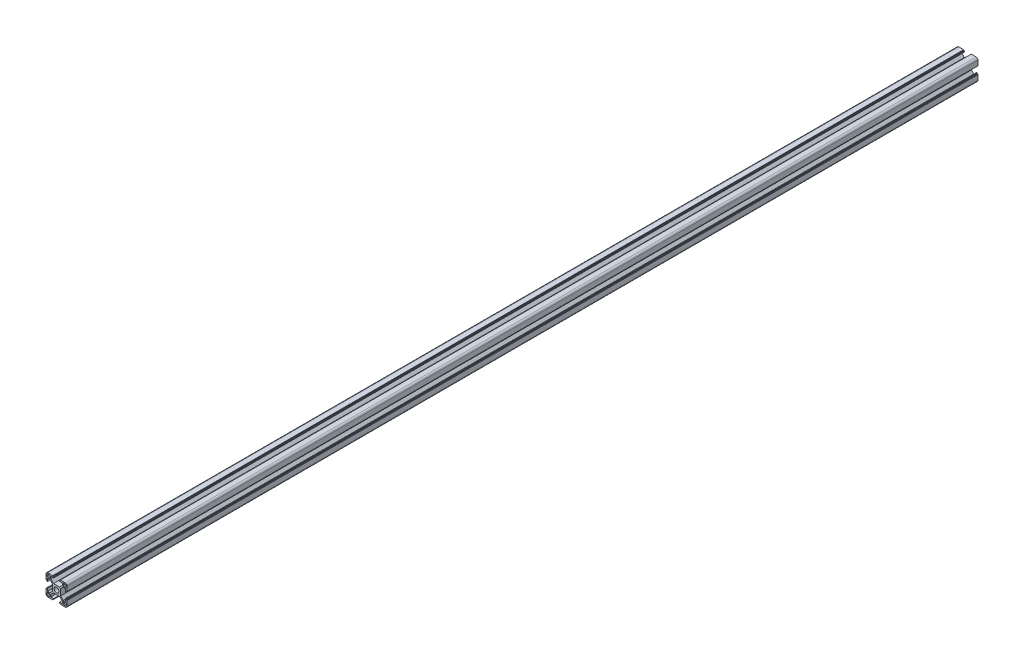
SolidWorks part; units mm, degrees
ref_plane "Front Plane" through (0, 0, 0) normal (0, 0, 1) x (1, 0, 0)
ref_plane "Top Plane" through (0, 0, 0) normal (0, 1, 0) x (1, 0, 0)
ref_plane "Right Plane" through (0, 0, 0) normal (1, 0, 0) x (0, 0, -1)
sketch "Sketch1" plane through (0, 0, 0) normal (0, 0, 1) x (1, 0, 0)
  line L0 (0, -5.8) -> (0, 5.8) construction
  line L1 (0, 0) -> (-15, 15) construction
  line L2 (-15, 15) -> (-5.2, 15)
  line L3 (-5.2, 15) -> (-5.2, 13.8083)
  line L4 (-5.2, 13.8083) -> (-4.1, 13.8083)
  line L5 (-4.1, 13.8083) -> (-4.1, 12.8)
  line L6 (-4.1, 12.8) -> (-8.25, 12.8)
  line L7 (-8.25, 12.8) -> (-8.25, 9.6642)
  line L8 (-8.25, 9.6642) -> (-4.3858, 5.8)
  line L9 (-4.3858, 5.8) -> (4.3858, 5.8)
  line L10 (-5.8, 4.3858) -> (-5.8, -4.3858)
  line L11 (-9.6642, 8.25) -> (-5.8, 4.3858)
  line L12 (-12.8, 8.25) -> (-9.6642, 8.25)
  line L13 (-12.8, 4.1) -> (-12.8, 8.25)
  line L14 (-13.8083, 4.1) -> (-12.8, 4.1)
  line L15 (-13.8083, 5.2) -> (-13.8083, 4.1)
  line L16 (-15, 5.2) -> (-13.8083, 5.2)
  line L17 (-15, 15) -> (-15, 5.2)
  line L18 (0, 0) -> (15, 15) construction
  line L19 (15, 15) -> (15, 5.2)
  line L20 (15, 5.2) -> (13.8083, 5.2)
  line L21 (13.8083, 5.2) -> (13.8083, 4.1)
  line L22 (13.8083, 4.1) -> (12.8, 4.1)
  line L23 (12.8, 4.1) -> (12.8, 8.25)
  line L24 (12.8, 8.25) -> (9.6642, 8.25)
  line L25 (9.6642, 8.25) -> (5.8, 4.3858)
  line L26 (5.8, 4.3858) -> (5.8, -4.3858)
  line L27 (8.25, 9.6642) -> (4.3858, 5.8)
  line L28 (8.25, 12.8) -> (8.25, 9.6642)
  line L29 (4.1, 12.8) -> (8.25, 12.8)
  line L30 (4.1, 13.8083) -> (4.1, 12.8)
  line L31 (5.2, 13.8083) -> (4.1, 13.8083)
  line L32 (5.2, 15) -> (5.2, 13.8083)
  line L33 (15, 15) -> (5.2, 15)
  line L34 (0, 0) -> (3.5826, 0) construction
  line L35 (0, 0) -> (15, -15) construction
  line L36 (0, 0) -> (-15, -15) construction
  line L37 (15, -15) -> (5.2, -15)
  line L38 (5.2, -15) -> (5.2, -13.8083)
  line L39 (5.2, -13.8083) -> (4.1, -13.8083)
  line L40 (4.1, -13.8083) -> (4.1, -12.8)
  line L41 (4.1, -12.8) -> (8.25, -12.8)
  line L42 (8.25, -12.8) -> (8.25, -9.6642)
  line L43 (8.25, -9.6642) -> (4.3858, -5.8)
  line L44 (9.6642, -8.25) -> (5.8, -4.3858)
  line L45 (12.8, -8.25) -> (9.6642, -8.25)
  line L46 (12.8, -4.1) -> (12.8, -8.25)
  line L47 (13.8083, -4.1) -> (12.8, -4.1)
  line L48 (13.8083, -5.2) -> (13.8083, -4.1)
  line L49 (15, -5.2) -> (13.8083, -5.2)
  line L50 (15, -15) -> (15, -5.2)
  line L51 (-15, -15) -> (-15, -5.2)
  line L52 (-15, -5.2) -> (-13.8083, -5.2)
  line L53 (-13.8083, -5.2) -> (-13.8083, -4.1)
  line L54 (-13.8083, -4.1) -> (-12.8, -4.1)
  line L55 (-12.8, -4.1) -> (-12.8, -8.25)
  line L56 (-12.8, -8.25) -> (-9.6642, -8.25)
  line L57 (-9.6642, -8.25) -> (-5.8, -4.3858)
  line L58 (-4.3858, -5.8) -> (4.3858, -5.8)
  line L59 (-8.25, -9.6642) -> (-4.3858, -5.8)
  line L60 (-8.25, -12.8) -> (-8.25, -9.6642)
  line L61 (-4.1, -12.8) -> (-8.25, -12.8)
  line L62 (-4.1, -13.8083) -> (-4.1, -12.8)
  line L63 (-5.2, -13.8083) -> (-4.1, -13.8083)
  line L64 (-5.2, -15) -> (-5.2, -13.8083)
  line L65 (-15, -15) -> (-5.2, -15)
  point P30 (0, 5.8)
  point P48 (5.8, 0)
  point P61 (-5.8, 0)
  dimension "D2" = 15
  dimension "D3" = 1
  dimension "D4" = 4.1
  dimension "D5" = 5.2
  dimension "D6" = 2.2
  dimension "D7" = 8.25
  dimension "D8" = 9.2
extrude "Boss-Extrude1" add sketch "Sketch1" along normal blind 250
sketch "Sketch2" plane through (0, 0, 250) normal (0, 0, 1) x (1, 0, 0)
  line L0 (0, 0) -> (0, 17.0054) construction
  line L1 (0, 0) -> (20.7717, 0) construction
  line L2 (-5.2, 15) -> (-15, 15) construction
  line L3 (-12.5, 13.5) -> (-10.5, 13.5)
  line L4 (-13.5, 12.5) -> (-13.5, 10.5)
  line L5 (-12.5, 9.5) -> (-10.5, 9.5)
  line L6 (-9.5, 12.5) -> (-9.5, 10.5)
  line L7 (-13.5, 13.5) -> (-9.5, 9.5) construction
  line L8 (-13.5, 9.5) -> (-9.5, 13.5) construction
  line L9 (-15, 15) -> (-15, 5.2) construction
  line L10 (13.5, 9.5) -> (9.5, 13.5) construction
  line L11 (13.5, 13.5) -> (9.5, 9.5) construction
  line L12 (9.5, 12.5) -> (9.5, 10.5)
  line L13 (12.5, 9.5) -> (10.5, 9.5)
  line L14 (13.5, 12.5) -> (13.5, 10.5)
  line L15 (12.5, 13.5) -> (10.5, 13.5)
  line L16 (13.5, -13.5) -> (9.5, -9.5) construction
  line L17 (13.5, -9.5) -> (9.5, -13.5) construction
  line L18 (-13.5, -9.5) -> (-9.5, -13.5) construction
  line L19 (-13.5, -13.5) -> (-9.5, -9.5) construction
  line L20 (12.5, -13.5) -> (10.5, -13.5)
  line L21 (13.5, -12.5) -> (13.5, -10.5)
  line L22 (12.5, -9.5) -> (10.5, -9.5)
  line L23 (9.5, -12.5) -> (9.5, -10.5)
  line L24 (-9.5, -12.5) -> (-9.5, -10.5)
  line L25 (-12.5, -9.5) -> (-10.5, -9.5)
  line L26 (-13.5, -12.5) -> (-13.5, -10.5)
  line L27 (-12.5, -13.5) -> (-10.5, -13.5)
  arc A0 (-12.5, 13.5) -> (-13.5, 12.5) centre (-12.5, 12.5) ccw
  arc A1 (-13.5, 10.5) -> (-12.5, 9.5) centre (-12.5, 10.5) ccw
  arc A2 (-10.5, 9.5) -> (-9.5, 10.5) centre (-10.5, 10.5) ccw
  arc A3 (-10.5, 13.5) -> (-9.5, 12.5) centre (-10.5, 12.5) cw
  arc A4 (10.5, 13.5) -> (9.5, 12.5) centre (10.5, 12.5) ccw
  arc A5 (10.5, 9.5) -> (9.5, 10.5) centre (10.5, 10.5) cw
  arc A6 (13.5, 10.5) -> (12.5, 9.5) centre (12.5, 10.5) cw
  arc A7 (12.5, 13.5) -> (13.5, 12.5) centre (12.5, 12.5) cw
  arc A8 (12.5, -13.5) -> (13.5, -12.5) centre (12.5, -12.5) ccw
  arc A9 (13.5, -10.5) -> (12.5, -9.5) centre (12.5, -10.5) ccw
  arc A10 (10.5, -9.5) -> (9.5, -10.5) centre (10.5, -10.5) ccw
  arc A11 (10.5, -13.5) -> (9.5, -12.5) centre (10.5, -12.5) cw
  arc A12 (-10.5, -13.5) -> (-9.5, -12.5) centre (-10.5, -12.5) ccw
  arc A13 (-10.5, -9.5) -> (-9.5, -10.5) centre (-10.5, -10.5) cw
  arc A14 (-13.5, -10.5) -> (-12.5, -9.5) centre (-12.5, -10.5) cw
  arc A15 (-12.5, -13.5) -> (-13.5, -12.5) centre (-12.5, -12.5) cw
  circle A16 centre (0, 0) radius 3.4
  point P3 (-11.5, 11.5)
  point P41 (11.5, 11.5)
  point P74 (11.5, -11.5)
  point P75 (-11.5, -11.5)
  dimension "D5" = 1
  dimension "D6" = 6.8
  dimension "D1" = 1.5
  dimension "D2" = 1.5
  dimension "D3" = 4
  dimension "D4" = 4
extrude "Cut-Extrude1" cut sketch "Sketch2" against normal through all
fillet "Fillet1" radius 2.5 4 edges at (-15, -15, 125) (15, -15, 125) (15, 15, 125) (-15, 15, 125)
fillet "Fillet2" radius 0.25 24 edges at (-13.8083, 5.2, 125) (-13.8083, 4.1, 125) (-15, 5.2, 125) (-13.8083, -4.1, 125) (-13.8083, -5.2, 125) (-15, -5.2, 125) (-5.2, -15, 125) (-5.2, -13.8083, 125) (-4.1, -13.8083, 125) (4.1, -13.8083, 125) (5.2, -13.8083, 125) (5.2, -15, 125) (13.8083, -5.2, 125) (13.8083, -4.1, 125) (15, -5.2, 125) (13.8083, 4.1, 125) (13.8083, 5.2, 125) (15, 5.2, 125) (-4.1, 13.8083, 125) (-5.2, 13.8083, 125) (4.1, 13.8083, 125) (5.2, 13.8083, 125) (5.2, 15, 125) (-5.2, 15, 125)
sketch "Sketch3" plane through (0, 0, 0) normal (0, 0, -1) x (-1, 0, 0)
  line L0 (-12.5, 13.5) -> (-10.5, 13.5) construction
  line L1 (-10.5, 9.5) -> (-12.5, 9.5) construction
  line L2 (-9.5, 12.5) -> (-9.5, 10.5) construction
  line L3 (-13.5, 10.5) -> (-13.5, 12.5) construction
  line L4 (-9.5, 12.5) -> (-9.5, 10.5)
  line L5 (-12.5, 13.5) -> (-10.5, 13.5)
  line L6 (-13.5, 10.5) -> (-13.5, 12.5)
  line L7 (-10.5, 9.5) -> (-12.5, 9.5)
  line L8 (10.5, 13.5) -> (12.5, 13.5) construction
  line L9 (9.5, 10.5) -> (9.5, 12.5) construction
  line L10 (13.5, 12.5) -> (13.5, 10.5) construction
  line L11 (12.5, 9.5) -> (10.5, 9.5) construction
  line L12 (12.5, 9.5) -> (10.5, 9.5)
  line L13 (13.5, 12.5) -> (13.5, 10.5)
  line L14 (9.5, 10.5) -> (9.5, 12.5)
  line L15 (10.5, 13.5) -> (12.5, 13.5)
  line L16 (9.5, -12.5) -> (9.5, -10.5) construction
  line L17 (12.5, -13.5) -> (10.5, -13.5) construction
  line L18 (13.5, -10.5) -> (13.5, -12.5) construction
  line L19 (10.5, -9.5) -> (12.5, -9.5) construction
  line L20 (9.5, -12.5) -> (9.5, -10.5)
  line L21 (12.5, -13.5) -> (10.5, -13.5)
  line L22 (13.5, -10.5) -> (13.5, -12.5)
  line L23 (10.5, -9.5) -> (12.5, -9.5)
  line L24 (-9.5, -10.5) -> (-9.5, -12.5) construction
  line L25 (-10.5, -13.5) -> (-12.5, -13.5) construction
  line L26 (-13.5, -12.5) -> (-13.5, -10.5) construction
  line L27 (-12.5, -9.5) -> (-10.5, -9.5) construction
  line L28 (-9.5, -10.5) -> (-9.5, -12.5)
  line L29 (-10.5, -13.5) -> (-12.5, -13.5)
  line L30 (-13.5, -12.5) -> (-13.5, -10.5)
  line L31 (-12.5, -9.5) -> (-10.5, -9.5)
  line L60 (12.8, 4.1) -> (13.5583, 4.1)
  line L61 (13.8083, 4.35) -> (13.8083, 4.95)
  line L62 (14.0583, 5.2) -> (14.75, 5.2)
  line L63 (15, 5.45) -> (15, 12.5)
  line L64 (12.5, 15) -> (5.45, 15)
  line L65 (5.2, 14.75) -> (5.2, 14.0583)
  line L66 (4.95, 13.8083) -> (4.35, 13.8083)
  line L67 (4.1, 13.5583) -> (4.1, 12.8)
  line L68 (4.1, 12.8) -> (8.25, 12.8)
  line L69 (8.25, 12.8) -> (8.25, 9.6642)
  line L70 (8.25, 9.6642) -> (4.3858, 5.8)
  line L71 (4.3858, 5.8) -> (-4.3858, 5.8)
  line L72 (-4.3858, 5.8) -> (-8.25, 9.6642)
  line L73 (-8.25, 9.6642) -> (-8.25, 12.8)
  line L74 (-8.25, 12.8) -> (-4.1, 12.8)
  line L75 (-4.1, 12.8) -> (-4.1, 13.5583)
  line L76 (-4.35, 13.8083) -> (-4.95, 13.8083)
  line L77 (-5.2, 14.0583) -> (-5.2, 14.75)
  line L78 (-5.45, 15) -> (-12.5, 15)
  line L79 (-15, 12.5) -> (-15, 5.45)
  line L80 (-14.75, 5.2) -> (-14.0583, 5.2)
  line L81 (-13.8083, 4.95) -> (-13.8083, 4.35)
  line L82 (-13.5583, 4.1) -> (-12.8, 4.1)
  line L83 (-12.8, 4.1) -> (-12.8, 8.25)
  line L84 (-12.8, 8.25) -> (-9.6642, 8.25)
  line L85 (-9.6642, 8.25) -> (-5.8, 4.3858)
  line L86 (-5.8, 4.3858) -> (-5.8, -4.3858)
  line L87 (-5.8, -4.3858) -> (-9.6642, -8.25)
  line L88 (-9.6642, -8.25) -> (-12.8, -8.25)
  line L89 (-12.8, -8.25) -> (-12.8, -4.1)
  line L90 (-12.8, -4.1) -> (-13.5583, -4.1)
  line L91 (-13.8083, -4.35) -> (-13.8083, -4.95)
  line L92 (-14.0583, -5.2) -> (-14.75, -5.2)
  line L93 (-15, -5.45) -> (-15, -12.5)
  line L94 (-12.5, -15) -> (-5.45, -15)
  line L95 (-5.2, -14.75) -> (-5.2, -14.0583)
  line L96 (-4.95, -13.8083) -> (-4.35, -13.8083)
  line L97 (-4.1, -13.5583) -> (-4.1, -12.8)
  line L98 (-4.1, -12.8) -> (-8.25, -12.8)
  line L99 (-8.25, -12.8) -> (-8.25, -9.6642)
  line L100 (-8.25, -9.6642) -> (-4.3858, -5.8)
  line L101 (-4.3858, -5.8) -> (4.3858, -5.8)
  line L102 (4.3858, -5.8) -> (8.25, -9.6642)
  line L103 (8.25, -9.6642) -> (8.25, -12.8)
  line L104 (8.25, -12.8) -> (4.1, -12.8)
  line L105 (4.1, -12.8) -> (4.1, -13.5583)
  line L106 (4.35, -13.8083) -> (4.95, -13.8083)
  line L107 (5.2, -14.0583) -> (5.2, -14.75)
  line L108 (5.45, -15) -> (12.5, -15)
  line L109 (15, -12.5) -> (15, -5.45)
  line L110 (14.75, -5.2) -> (14.0583, -5.2)
  line L111 (13.8083, -4.95) -> (13.8083, -4.35)
  line L112 (13.5583, -4.1) -> (12.8, -4.1)
  line L113 (12.8, -4.1) -> (12.8, -8.25)
  line L114 (12.8, -8.25) -> (9.6642, -8.25)
  line L115 (9.6642, -8.25) -> (5.8, -4.3858)
  line L116 (5.8, -4.3858) -> (5.8, 4.3858)
  line L117 (5.8, 4.3858) -> (9.6642, 8.25)
  line L118 (9.6642, 8.25) -> (12.8, 8.25)
  line L119 (12.8, 8.25) -> (12.8, 4.1)
  line L120 (12.8, 4.1) -> (13.5583, 4.1)
  line L121 (13.8083, 4.35) -> (13.8083, 4.95)
  line L122 (14.0583, 5.2) -> (14.75, 5.2)
  line L123 (15, 5.45) -> (15, 12.5)
  line L124 (12.5, 15) -> (5.45, 15)
  line L125 (5.2, 14.75) -> (5.2, 14.0583)
  line L126 (4.95, 13.8083) -> (4.35, 13.8083)
  line L127 (4.1, 13.5583) -> (4.1, 12.8)
  line L128 (4.1, 12.8) -> (8.25, 12.8)
  line L129 (8.25, 12.8) -> (8.25, 9.6642)
  line L130 (8.25, 9.6642) -> (4.3858, 5.8)
  line L131 (4.3858, 5.8) -> (-4.3858, 5.8)
  line L132 (-4.3858, 5.8) -> (-8.25, 9.6642)
  line L133 (-8.25, 9.6642) -> (-8.25, 12.8)
  line L134 (-8.25, 12.8) -> (-4.1, 12.8)
  line L135 (-4.1, 12.8) -> (-4.1, 13.5583)
  line L136 (-4.35, 13.8083) -> (-4.95, 13.8083)
  line L137 (-5.2, 14.0583) -> (-5.2, 14.75)
  line L138 (-5.45, 15) -> (-12.5, 15)
  line L139 (-15, 12.5) -> (-15, 5.45)
  line L140 (-14.75, 5.2) -> (-14.0583, 5.2)
  line L141 (-13.8083, 4.95) -> (-13.8083, 4.35)
  line L142 (-13.5583, 4.1) -> (-12.8, 4.1)
  line L143 (-12.8, 4.1) -> (-12.8, 8.25)
  line L144 (-12.8, 8.25) -> (-9.6642, 8.25)
  line L145 (-9.6642, 8.25) -> (-5.8, 4.3858)
  line L146 (-5.8, 4.3858) -> (-5.8, -4.3858)
  line L147 (-5.8, -4.3858) -> (-9.6642, -8.25)
  line L148 (-9.6642, -8.25) -> (-12.8, -8.25)
  line L149 (-12.8, -8.25) -> (-12.8, -4.1)
  line L150 (-12.8, -4.1) -> (-13.5583, -4.1)
  line L151 (-13.8083, -4.35) -> (-13.8083, -4.95)
  line L152 (-14.0583, -5.2) -> (-14.75, -5.2)
  line L153 (-15, -5.45) -> (-15, -12.5)
  line L154 (-12.5, -15) -> (-5.45, -15)
  line L155 (-5.2, -14.75) -> (-5.2, -14.0583)
  line L156 (-4.95, -13.8083) -> (-4.35, -13.8083)
  line L157 (-4.1, -13.5583) -> (-4.1, -12.8)
  line L158 (-4.1, -12.8) -> (-8.25, -12.8)
  line L159 (-8.25, -12.8) -> (-8.25, -9.6642)
  line L160 (-8.25, -9.6642) -> (-4.3858, -5.8)
  line L161 (-4.3858, -5.8) -> (4.3858, -5.8)
  line L162 (4.3858, -5.8) -> (8.25, -9.6642)
  line L163 (8.25, -9.6642) -> (8.25, -12.8)
  line L164 (8.25, -12.8) -> (4.1, -12.8)
  line L165 (4.1, -12.8) -> (4.1, -13.5583)
  line L166 (4.35, -13.8083) -> (4.95, -13.8083)
  line L167 (5.2, -14.0583) -> (5.2, -14.75)
  line L168 (5.45, -15) -> (12.5, -15)
  line L169 (15, -12.5) -> (15, -5.45)
  line L170 (14.75, -5.2) -> (14.0583, -5.2)
  line L171 (13.8083, -4.95) -> (13.8083, -4.35)
  line L172 (13.5583, -4.1) -> (12.8, -4.1)
  line L173 (12.8, -4.1) -> (12.8, -8.25)
  line L174 (12.8, -8.25) -> (9.6642, -8.25)
  line L175 (9.6642, -8.25) -> (5.8, -4.3858)
  line L176 (5.8, -4.3858) -> (5.8, 4.3858)
  line L177 (5.8, 4.3858) -> (9.6642, 8.25)
  line L178 (9.6642, 8.25) -> (12.8, 8.25)
  line L179 (12.8, 8.25) -> (12.8, 4.1)
  circle A0 centre (0, 0) radius 3.4 construction
  circle A1 centre (0, 0) radius 3.4
  arc A2 (-12.5, 13.5) -> (-13.5, 12.5) centre (-12.5, 12.5) ccw construction
  arc A3 (-9.5, 12.5) -> (-10.5, 13.5) centre (-10.5, 12.5) ccw construction
  arc A4 (-13.5, 10.5) -> (-12.5, 9.5) centre (-12.5, 10.5) ccw construction
  arc A5 (-10.5, 9.5) -> (-9.5, 10.5) centre (-10.5, 10.5) ccw construction
  arc A6 (-9.5, 12.5) -> (-10.5, 13.5) centre (-10.5, 12.5) ccw
  arc A7 (-12.5, 13.5) -> (-13.5, 12.5) centre (-12.5, 12.5) ccw
  arc A8 (-13.5, 10.5) -> (-12.5, 9.5) centre (-12.5, 10.5) ccw
  arc A9 (-10.5, 9.5) -> (-9.5, 10.5) centre (-10.5, 10.5) ccw
  arc A10 (13.5, 12.5) -> (12.5, 13.5) centre (12.5, 12.5) ccw construction
  arc A11 (10.5, 13.5) -> (9.5, 12.5) centre (10.5, 12.5) ccw construction
  arc A12 (12.5, 9.5) -> (13.5, 10.5) centre (12.5, 10.5) ccw construction
  arc A13 (9.5, 10.5) -> (10.5, 9.5) centre (10.5, 10.5) ccw construction
  arc A14 (9.5, 10.5) -> (10.5, 9.5) centre (10.5, 10.5) ccw
  arc A15 (12.5, 9.5) -> (13.5, 10.5) centre (12.5, 10.5) ccw
  arc A16 (10.5, 13.5) -> (9.5, 12.5) centre (10.5, 12.5) ccw
  arc A17 (13.5, 12.5) -> (12.5, 13.5) centre (12.5, 12.5) ccw
  arc A18 (10.5, -9.5) -> (9.5, -10.5) centre (10.5, -10.5) ccw construction
  arc A19 (9.5, -12.5) -> (10.5, -13.5) centre (10.5, -12.5) ccw construction
  arc A20 (12.5, -13.5) -> (13.5, -12.5) centre (12.5, -12.5) ccw construction
  arc A21 (13.5, -10.5) -> (12.5, -9.5) centre (12.5, -10.5) ccw construction
  arc A22 (10.5, -9.5) -> (9.5, -10.5) centre (10.5, -10.5) ccw
  arc A23 (9.5, -12.5) -> (10.5, -13.5) centre (10.5, -12.5) ccw
  arc A24 (12.5, -13.5) -> (13.5, -12.5) centre (12.5, -12.5) ccw
  arc A25 (13.5, -10.5) -> (12.5, -9.5) centre (12.5, -10.5) ccw
  arc A26 (-9.5, -10.5) -> (-10.5, -9.5) centre (-10.5, -10.5) ccw construction
  arc A27 (-10.5, -13.5) -> (-9.5, -12.5) centre (-10.5, -12.5) ccw construction
  arc A28 (13.5583, 4.1) -> (13.8083, 4.35) centre (13.5583, 4.35) ccw
  arc A29 (14.0583, 5.2) -> (13.8083, 4.95) centre (14.0583, 4.95) ccw
  arc A30 (14.75, 5.2) -> (15, 5.45) centre (14.75, 5.45) ccw
  arc A31 (15, 12.5) -> (12.5, 15) centre (12.5, 12.5) ccw
  arc A32 (5.45, 15) -> (5.2, 14.75) centre (5.45, 14.75) ccw
  arc A33 (4.95, 13.8083) -> (5.2, 14.0583) centre (4.95, 14.0583) ccw
  arc A34 (4.35, 13.8083) -> (4.1, 13.5583) centre (4.35, 13.5583) ccw
  arc A35 (-4.1, 13.5583) -> (-4.35, 13.8083) centre (-4.35, 13.5583) ccw
  arc A36 (-5.2, 14.0583) -> (-4.95, 13.8083) centre (-4.95, 14.0583) ccw
  arc A37 (-5.2, 14.75) -> (-5.45, 15) centre (-5.45, 14.75) ccw
  arc A38 (-12.5, 15) -> (-15, 12.5) centre (-12.5, 12.5) ccw
  arc A39 (-15, 5.45) -> (-14.75, 5.2) centre (-14.75, 5.45) ccw
  arc A40 (-13.8083, 4.95) -> (-14.0583, 5.2) centre (-14.0583, 4.95) ccw
  arc A41 (-13.8083, 4.35) -> (-13.5583, 4.1) centre (-13.5583, 4.35) ccw
  arc A42 (-13.5583, -4.1) -> (-13.8083, -4.35) centre (-13.5583, -4.35) ccw
  arc A43 (-14.0583, -5.2) -> (-13.8083, -4.95) centre (-14.0583, -4.95) ccw
  arc A44 (-14.75, -5.2) -> (-15, -5.45) centre (-14.75, -5.45) ccw
  arc A45 (-15, -12.5) -> (-12.5, -15) centre (-12.5, -12.5) ccw
  arc A46 (-5.45, -15) -> (-5.2, -14.75) centre (-5.45, -14.75) ccw
  arc A47 (-4.95, -13.8083) -> (-5.2, -14.0583) centre (-4.95, -14.0583) ccw
  arc A48 (-4.35, -13.8083) -> (-4.1, -13.5583) centre (-4.35, -13.5583) ccw
  arc A49 (4.1, -13.5583) -> (4.35, -13.8083) centre (4.35, -13.5583) ccw
  arc A50 (5.2, -14.0583) -> (4.95, -13.8083) centre (4.95, -14.0583) ccw
  arc A51 (5.2, -14.75) -> (5.45, -15) centre (5.45, -14.75) ccw
  arc A52 (12.5, -15) -> (15, -12.5) centre (12.5, -12.5) ccw
  arc A53 (15, -5.45) -> (14.75, -5.2) centre (14.75, -5.45) ccw
  arc A54 (13.8083, -4.95) -> (14.0583, -5.2) centre (14.0583, -4.95) ccw
  arc A55 (13.8083, -4.35) -> (13.5583, -4.1) centre (13.5583, -4.35) ccw
  arc A56 (13.5583, 4.1) -> (13.8083, 4.35) centre (13.5583, 4.35) ccw
  arc A57 (14.0583, 5.2) -> (13.8083, 4.95) centre (14.0583, 4.95) ccw
  arc A58 (14.75, 5.2) -> (15, 5.45) centre (14.75, 5.45) ccw
  arc A59 (15, 12.5) -> (12.5, 15) centre (12.5, 12.5) ccw
  arc A60 (5.45, 15) -> (5.2, 14.75) centre (5.45, 14.75) ccw
  arc A61 (4.95, 13.8083) -> (5.2, 14.0583) centre (4.95, 14.0583) ccw
  arc A62 (4.35, 13.8083) -> (4.1, 13.5583) centre (4.35, 13.5583) ccw
  arc A63 (-4.1, 13.5583) -> (-4.35, 13.8083) centre (-4.35, 13.5583) ccw
  arc A64 (-5.2, 14.0583) -> (-4.95, 13.8083) centre (-4.95, 14.0583) ccw
  arc A65 (-5.2, 14.75) -> (-5.45, 15) centre (-5.45, 14.75) ccw
  arc A66 (-12.5, 15) -> (-15, 12.5) centre (-12.5, 12.5) ccw
  arc A67 (-15, 5.45) -> (-14.75, 5.2) centre (-14.75, 5.45) ccw
  arc A68 (-13.8083, 4.95) -> (-14.0583, 5.2) centre (-14.0583, 4.95) ccw
  arc A69 (-13.8083, 4.35) -> (-13.5583, 4.1) centre (-13.5583, 4.35) ccw
  arc A70 (-13.5583, -4.1) -> (-13.8083, -4.35) centre (-13.5583, -4.35) ccw
  arc A71 (-14.0583, -5.2) -> (-13.8083, -4.95) centre (-14.0583, -4.95) ccw
  arc A72 (-14.75, -5.2) -> (-15, -5.45) centre (-14.75, -5.45) ccw
  arc A73 (-15, -12.5) -> (-12.5, -15) centre (-12.5, -12.5) ccw
  arc A74 (-5.45, -15) -> (-5.2, -14.75) centre (-5.45, -14.75) ccw
  arc A75 (-4.95, -13.8083) -> (-5.2, -14.0583) centre (-4.95, -14.0583) ccw
  arc A76 (-4.35, -13.8083) -> (-4.1, -13.5583) centre (-4.35, -13.5583) ccw
  arc A77 (4.1, -13.5583) -> (4.35, -13.8083) centre (4.35, -13.5583) ccw
  arc A78 (5.2, -14.0583) -> (4.95, -13.8083) centre (4.95, -14.0583) ccw
  arc A79 (5.2, -14.75) -> (5.45, -15) centre (5.45, -14.75) ccw
  arc A80 (12.5, -15) -> (15, -12.5) centre (12.5, -12.5) ccw
  arc A81 (15, -5.45) -> (14.75, -5.2) centre (14.75, -5.45) ccw
  arc A82 (13.8083, -4.95) -> (14.0583, -5.2) centre (14.0583, -4.95) ccw
  arc A83 (13.8083, -4.35) -> (13.5583, -4.1) centre (13.5583, -4.35) ccw
  arc A84 (-13.5, -12.5) -> (-12.5, -13.5) centre (-12.5, -12.5) ccw construction
  arc A85 (-12.5, -9.5) -> (-13.5, -10.5) centre (-12.5, -10.5) ccw construction
  arc A86 (-9.5, -10.5) -> (-10.5, -9.5) centre (-10.5, -10.5) ccw
  arc A87 (-10.5, -13.5) -> (-9.5, -12.5) centre (-10.5, -12.5) ccw
  arc A88 (-13.5, -12.5) -> (-12.5, -13.5) centre (-12.5, -12.5) ccw
  arc A89 (-12.5, -9.5) -> (-13.5, -10.5) centre (-12.5, -10.5) ccw
  dimension "D1" = 0
extrude "Boss-Extrude2" add sketch "Sketch3" along normal blind 1050
